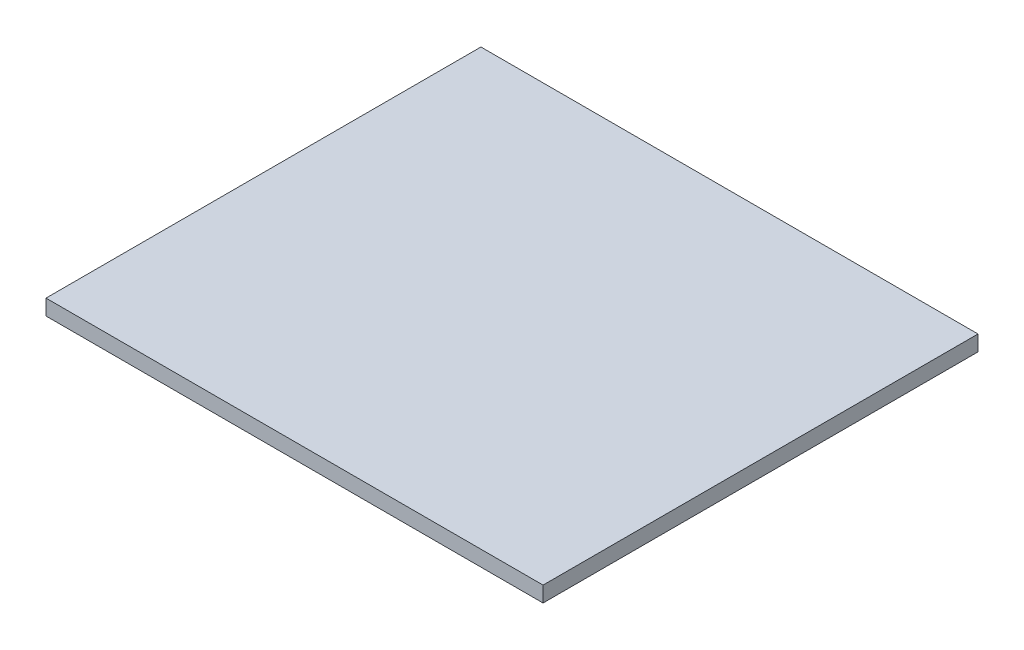
SolidWorks part; units mm, degrees
material "Delrin 2700 NC010, Low Viscosity Acetal Copolymer (SS)"
ref_plane "Front Plane" through (0, 0, 0) normal (0, 0, 1) x (1, 0, 0)
ref_plane "Top Plane" through (0, 0, 0) normal (0, 1, 0) x (1, 0, 0)
ref_plane "Right Plane" through (0, 0, 0) normal (1, 0, 0) x (0, 0, -1)
sketch "Sketch1" plane through (0, 0, 0) normal (0, 1, 0) x (1, 0, 0)
  line L1 (-203.2, 177.8) -> (203.2, 177.8)
  line L2 (-203.2, 177.8) -> (-203.2, -177.8)
  line L3 (-203.2, -177.8) -> (203.2, -177.8)
  line L4 (203.2, 177.8) -> (203.2, -177.8)
  line L5 (-203.2, 177.8) -> (203.2, -177.8) construction
  line L6 (-203.2, -177.8) -> (203.2, 177.8) construction
  point P0 (0, 0)
  dimension "D1" = 406.4
  dimension "D2" = 355.6
extrude "Boss-Extrude1" add sketch "Sketch1" along normal blind 12.7
sketch "Sketch2" plane through (0, 0, 0) normal (0, 1, 0) x (1, 0, 0)
  line L0 (-203.2, 0) -> (203.2, 0) construction
  line L4 (203.2, -177.8) -> (203.2, 177.8)
  line L5 (203.2, 177.8) -> (-203.2, 177.8)
  line L6 (-203.2, 177.8) -> (-203.2, -177.8)
  line L7 (-203.2, -177.8) -> (203.2, -177.8)
  line L8 (203.2, -177.8) -> (203.2, 177.8) construction
  line L9 (203.2, 177.8) -> (-203.2, 177.8) construction
  line L10 (-203.2, 177.8) -> (-203.2, -177.8) construction
  line L11 (-203.2, -177.8) -> (203.2, -177.8) construction
  line L13 (0, -177.8) -> (0, 177.8) construction
  line L14 (53.2, 35) -> (53.2, -35) construction
  line L15 (43.2, 35) -> (63.2, 35) construction
  line L16 (43.2, 35) -> (43.2, -35) construction
  line L17 (43.2, -35) -> (63.2, -35) construction
  line L18 (63.2, 35) -> (63.2, -35) construction
  line L19 (43.2, 0) -> (63.2, 0) construction
  circle A0 centre (43.2, 35) radius 3 construction
  circle A1 centre (63.2, 35) radius 3 construction
  circle A2 centre (63.2, -35) radius 3 construction
  circle A3 centre (43.2, -35) radius 3 construction
  point P22 (43.2, 0)
  dimension "D5" = 6
  dimension "D2" = 150
  dimension "D6" = 20
  dimension "D7" = 70
  dimension "D1" = 0
equation "\"Motor Assembly Position\"= 4in"
equation "\"Motor Mount Position\"= 2in"
